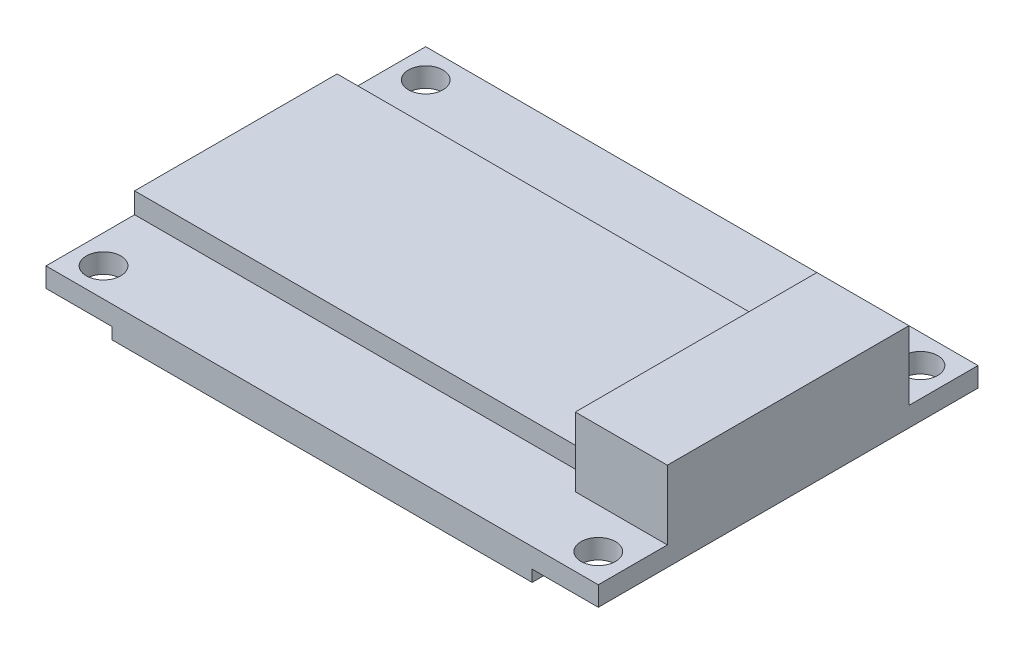
SolidWorks part; units mm, degrees
ref_plane "Front Plane" through (0, 0, 0) normal (0, 0, 1) x (1, 0, 0)
ref_plane "Top Plane" through (0, 0, 0) normal (0, 1, 0) x (1, 0, 0)
ref_plane "Right Plane" through (0, 0, 0) normal (1, 0, 0) x (0, 0, -1)
sketch "Sketch1" plane through (0, 0, 0) normal (0, 1, 0) x (1, 0, 0)
  line L1 (0, 0) -> (48, 0)
  line L2 (0, 0) -> (0, 33)
  line L3 (0, 33) -> (48, 33)
  line L4 (48, 0) -> (48, 33)
  dimension "D1" = 48
  dimension "D2" = 33
extrude "Boss-Extrude1" add sketch "Sketch1" along normal blind 1.7
sketch "Sketch2" plane through (0, 1.7, 0) normal (0, 1, 0) x (1, 0, 0)
  line L0 (48, 16.5) -> (40, 16.5) construction
  line L1 (40, 27) -> (48, 27)
  line L2 (40, 27) -> (40, 6)
  line L3 (40, 6) -> (48, 6)
  line L4 (48, 27) -> (48, 6)
  line L5 (48, 0) -> (48, 33) construction
  dimension "D1" = 21
  dimension "D2" = 8
extrude "Boss-Extrude2" add sketch "Sketch2" along normal blind 6
sketch "Sketch3" plane through (0, 1.7, 0) normal (0, 1, 0) x (1, 0, 0)
  line L0 (2.5, 0) -> (2.5, 2.5) construction
  line L1 (0, 0) -> (48, 0) construction
  line L2 (2.5, 2.5) -> (0, 2.5) construction
  line L3 (0, 33) -> (0, 0) construction
  line L4 (1, 2.5) -> (2.5, 2.5) construction
  line L5 (0, 16.5) -> (6.6136, 16.5) construction
  line L6 (24, 0) -> (24, 7.8568) construction
  circle A0 centre (2.5, 2.5) radius 1.5
  circle A1 centre (45.5, 2.5) radius 1.5
  circle A2 centre (45.5, 30.5) radius 1.5
  circle A3 centre (2.5, 30.5) radius 1.5
  dimension "D2" = 3
  dimension "D1" = 2.5
extrude "Cut-Extrude1" cut sketch "Sketch3" against normal through all
sketch "Sketch4" plane through (0, 0, 0) normal (0, -1, 0) x (-1, 0, 0)
  line L0 (-48, 16.5) -> (0, 16.5) construction
  line L1 (-48, 0) -> (-48, 33) construction
  line L2 (0, 33) -> (0, 0) construction
  line L3 (0, 0) -> (-48, 0) construction
  line L4 (-5.75, 33) -> (-42.25, 33)
  line L5 (-5.75, 33) -> (-5.75, 0)
  line L6 (-5.75, 0) -> (-42.25, 0)
  line L7 (-42.25, 33) -> (-42.25, 0)
  line L8 (-5.75, 33) -> (-42.25, 0) construction
  line L9 (-5.75, 0) -> (-42.25, 33) construction
  point P6 (-24, 16.5)
  dimension "D1" = 36.5
extrude "Boss-Extrude3" add sketch "Sketch4" along normal blind 1
sketch "Sketch5" plane through (0, -1, 0) normal (0, -1, 0) x (-1, 0, 0)
  line L0 (-42.25, 16.5) -> (-5.75, 16.5) construction
  line L1 (-42.25, 33) -> (-42.25, 0) construction
  line L2 (-5.75, 0) -> (-5.75, 33) construction
  line L4 (-12.75, 2.5) -> (-40.75, 2.5)
  line L5 (-12.75, 2.5) -> (-12.75, 30.5)
  line L6 (-12.75, 30.5) -> (-40.75, 30.5)
  line L7 (-40.75, 2.5) -> (-40.75, 30.5)
  line L8 (-12.75, 2.5) -> (-40.75, 30.5) construction
  line L9 (-12.75, 30.5) -> (-40.75, 2.5) construction
  point P6 (-26.75, 16.5)
  dimension "D1" = 28
  dimension "D2" = 1.5
sketch "Sketch6" plane through (0, 1.7, 0) normal (0, 1, 0) x (1, 0, 0)
  line L0 (0, 16.5) -> (40, 16.5) construction
  line L1 (0, 33) -> (0, 0) construction
  line L2 (40, 27) -> (40, 6) construction
  line L4 (40, 7.7) -> (0, 7.7)
  line L5 (40, 7.7) -> (40, 25.3)
  line L6 (40, 25.3) -> (0, 25.3)
  line L7 (0, 7.7) -> (0, 25.3)
  line L8 (40, 7.7) -> (0, 25.3) construction
  line L9 (40, 25.3) -> (0, 7.7) construction
  point P6 (20, 16.5)
  dimension "D1" = 17.6
extrude "Boss-Extrude4" add sketch "Sketch6" along normal blind 1.8
